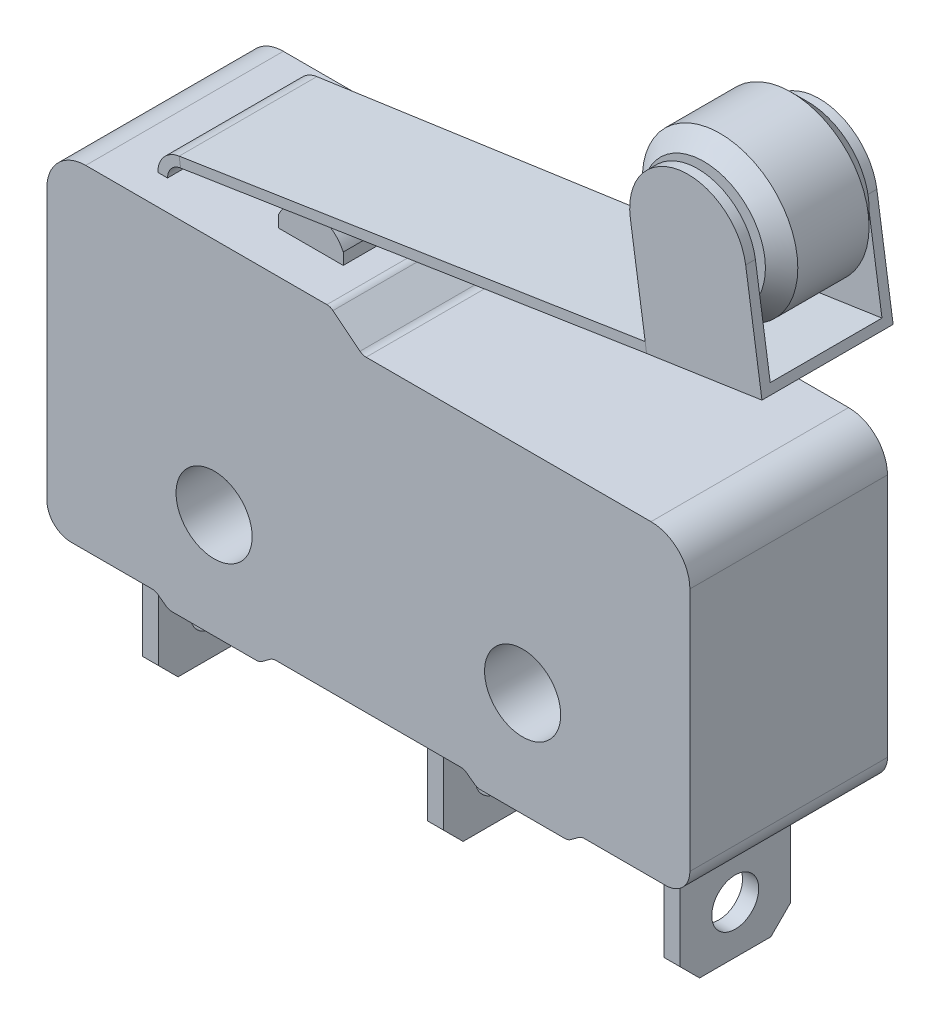
SolidWorks part; units mm, degrees
ref_plane "前视基准面" through (0, 0, 0) normal (0, 0, 1) x (1, 0, 0)
ref_plane "上视基准面" through (0, 0, 0) normal (0, 1, 0) x (1, 0, 0)
ref_plane "右视基准面" through (0, 0, 0) normal (1, 0, 0) x (0, 0, -1)
sketch "草图1" plane through (0, 0, 0) normal (0, 0, 1) x (1, 0, 0)
  line B0 (-3.0625, -6.8375) -> (-3.5625, -6.8375)
  line B1 (-3.5625, -6.2375) -> (-3.0625, -6.2375)
  line B2 (-3.0625, -6.8375) -> (-3.0625, -6.2375)
  line B3 (-3.5625, -6.8375) -> (-3.5625, -6.2375)
  line B4 (-3.0625, -6.2375) -> (-3.0625, -2.9375)
  line B5 (-3.5625, -6.2375) -> (-3.5625, -2.9375)
  line B6 (13.0375, -6.8375) -> (12.5375, -6.8375)
  line B7 (12.5375, -6.8375) -> (12.5375, -6.2375)
  line B8 (12.5375, -6.2375) -> (13.0375, -6.2375)
  line B9 (13.0375, -6.8375) -> (13.0375, -6.2375)
  line B10 (13.0375, -6.2375) -> (13.0375, -2.9375)
  line B11 (12.5375, -6.2375) -> (12.5375, -2.9375)
  line B12 (5.7375, -6.8375) -> (5.2375, -6.8375)
  line B13 (5.2375, -6.8375) -> (5.2375, -6.2375)
  line B14 (5.2375, -6.2375) -> (5.7375, -6.2375)
  line B15 (5.7375, -6.8375) -> (5.7375, -6.2375)
  line B16 (5.7375, -6.2375) -> (5.7375, -2.9375)
  line B17 (5.2375, -6.2375) -> (5.2375, -2.9375)
  line B18 (-2.6625, 6.5625) -> (-2.6625, 5.5625)
  line B19 (-2.3625, 6.5625) -> (-2.3625, 5.5625)
  line B20 (-1.9585, 7.8313) -> (-2.0029, 8.128)
  line B21 (-2.0029, 8.128) -> (1.8209, 8.6995)
  line B22 (1.8209, 8.6995) -> (1.8652, 8.4028)
  line B23 (1.8652, 8.4028) -> (-1.9585, 7.8313)
  line B24 (2.3154, 8.7734) -> (2.3597, 8.4767)
  line B25 (1.8209, 8.6995) -> (1.8704, 8.7069)
  line B26 (1.8704, 8.7069) -> (1.9301, 8.7158)
  line B27 (1.9301, 8.7158) -> (1.9968, 8.7258)
  line B28 (1.9968, 8.7258) -> (2.0673, 8.7363)
  line B29 (2.0673, 8.7363) -> (2.1379, 8.7469)
  line B30 (2.1379, 8.7469) -> (2.205, 8.7569)
  line B31 (2.205, 8.7569) -> (2.2652, 8.7659)
  line B32 (2.2652, 8.7659) -> (2.3154, 8.7734)
  line B33 (2.3597, 8.4767) -> (2.3095, 8.4692)
  line B34 (2.3095, 8.4692) -> (2.2493, 8.4602)
  line B35 (2.2493, 8.4602) -> (2.1822, 8.4502)
  line B36 (2.1822, 8.4502) -> (2.1116, 8.4396)
  line B37 (2.1116, 8.4396) -> (2.0412, 8.4291)
  line B38 (2.0412, 8.4291) -> (1.9744, 8.4191)
  line B39 (1.9744, 8.4191) -> (1.9147, 8.4102)
  line B40 (1.9147, 8.4102) -> (1.8652, 8.4028)
  line B41 (8.8923, 9.7563) -> (8.9367, 9.4596)
  line B42 (2.3154, 8.7734) -> (8.8923, 9.7563)
  line B43 (8.9367, 9.4596) -> (2.3597, 8.4767)
  line B44 (9.3869, 9.8302) -> (9.4312, 9.5335)
  line B45 (8.8923, 9.7563) -> (8.9367, 9.763)
  line B46 (8.9367, 9.763) -> (8.9954, 9.7717)
  line B47 (8.9954, 9.7717) -> (9.0643, 9.782)
  line B48 (9.0643, 9.782) -> (9.1386, 9.7931)
  line B49 (9.1386, 9.7931) -> (9.213, 9.8042)
  line B50 (9.213, 9.8042) -> (9.2823, 9.8146)
  line B51 (9.2823, 9.8146) -> (9.3416, 9.8235)
  line B52 (9.3416, 9.8235) -> (9.3869, 9.8302)
  line B53 (9.4312, 9.5335) -> (9.386, 9.5268)
  line B54 (9.386, 9.5268) -> (9.3266, 9.5179)
  line B55 (9.3266, 9.5179) -> (9.2573, 9.5075)
  line B56 (9.2573, 9.5075) -> (9.1829, 9.4964)
  line B57 (9.1829, 9.4964) -> (9.1087, 9.4853)
  line B58 (9.1087, 9.4853) -> (9.0398, 9.475)
  line B59 (9.0398, 9.475) -> (8.9811, 9.4663)
  line B60 (8.9811, 9.4663) -> (8.9367, 9.4596)
  line B61 (11.3926, 10.13) -> (11.4369, 9.8333)
  line B62 (9.3869, 9.8302) -> (11.3926, 10.13)
  line B63 (11.4369, 9.8333) -> (9.4312, 9.5335)
  line B64 (15.8284, 10.894) -> (12.2679, 10.3619)
  line B65 (15.8284, 10.894) -> (15.8399, 10.8169)
  line B66 (15.8399, 10.8169) -> (15.851, 10.7426)
  line B67 (15.851, 10.7426) -> (15.8612, 10.6742)
  line B68 (15.8612, 10.6742) -> (15.8702, 10.6143)
  line B69 (15.8702, 10.6143) -> (15.8775, 10.5651)
  line B70 (15.8775, 10.5651) -> (15.883, 10.5285)
  line B71 (15.883, 10.5285) -> (15.8864, 10.506)
  line B72 (15.8864, 10.506) -> (15.8875, 10.4984)
  line B73 (12.2827, 10.263) -> (12.2809, 10.2752)
  line B74 (12.2809, 10.2752) -> (12.2791, 10.2874)
  line B75 (12.2791, 10.2874) -> (12.2772, 10.2997)
  line B76 (12.2772, 10.2997) -> (12.2754, 10.3121)
  line B77 (12.2754, 10.3121) -> (12.2735, 10.3245)
  line B78 (12.2735, 10.3245) -> (12.2717, 10.3369)
  line B79 (12.2717, 10.3369) -> (12.2698, 10.3494)
  line B80 (12.2698, 10.3494) -> (12.2679, 10.3619)
  line B81 (12.2827, 10.263) -> (12.281, 10.2628)
  line B82 (15.8875, 10.4984) -> (11.8823, 9.8999)
  line B83 (11.3926, 10.13) -> (11.4165, 10.1336)
  line B84 (11.4165, 10.1336) -> (11.4647, 10.1408)
  line B85 (11.4647, 10.1408) -> (11.5346, 10.1512)
  line B86 (11.5346, 10.1512) -> (11.622, 10.1643)
  line B87 (11.622, 10.1643) -> (11.7219, 10.1792)
  line B88 (11.7219, 10.1792) -> (11.8285, 10.1951)
  line B89 (11.8285, 10.1951) -> (11.9357, 10.2112)
  line B90 (11.9357, 10.2112) -> (12.0372, 10.2263)
  line B91 (12.0372, 10.2263) -> (12.1272, 10.2398)
  line B92 (12.1272, 10.2398) -> (12.2005, 10.2507)
  line B93 (12.2005, 10.2507) -> (12.2528, 10.2585)
  line B94 (12.2528, 10.2585) -> (12.281, 10.2628)
  line B95 (11.8823, 9.8999) -> (11.8006, 9.8876)
  line B96 (11.8006, 9.8876) -> (11.7217, 9.8758)
  line B97 (11.7217, 9.8758) -> (11.6481, 9.8648)
  line B98 (11.6481, 9.8648) -> (11.5824, 9.855)
  line B99 (11.5824, 9.855) -> (11.5268, 9.8467)
  line B100 (11.5268, 9.8467) -> (11.4831, 9.8402)
  line B101 (11.4831, 9.8402) -> (11.4528, 9.8357)
  line B102 (11.4528, 9.8357) -> (11.4369, 9.8333)
  line B103 (12.2679, 10.3619) -> (11.8245, 13.329)
  line B104 (15.3849, 13.8611) -> (15.8284, 10.894)
  line B105 (0.6875, 7.3625) -> (0.6875, 7.7208)
  line B106 (2.6875, 7.7208) -> (2.6875, 7.3625)
  line B107 (8.0461, -3.1801) -> (7.7914, -2.9949)
  line B108 (7.7125, -2.9538) -> (7.7125, 0)
  line B109 (11.3375, 0) -> (11.3375, -2.9538)
  line B110 (11.0039, -3.1801) -> (11.2586, -2.9949)
  line B111 (8.2226, -3.2375) -> (10.8274, -3.2375)
  line B112 (-1.8125, -2.9538) -> (-1.8125, 0)
  line B113 (1.8125, 0) -> (1.8125, -2.9538)
  line B114 (1.4789, -3.1801) -> (1.7336, -2.9949)
  line B115 (-1.3024, -3.2375) -> (1.3024, -3.2375)
  line B116 (-1.4789, -3.1801) -> (-1.7336, -2.9949)
  line B117 (-2.7625, 6.5625) -> (-2.2125, 6.5625)
  line B118 (-2.7625, 5.5625) -> (-2.7625, 6.5625)
  line B119 (-2.2125, 5.5625) -> (-2.7625, 5.5625)
  line B120 (-2.2125, 6.5625) -> (-2.2125, 5.5625)
  line B121 (12.2347, -2.683) -> (12.0611, -2.683)
  line B122 (12.0611, -2.683) -> (12.0611, -1.283)
  line B123 (12.0611, -1.283) -> (12.3254, -1.283)
  line B124 (12.3254, -1.283) -> (12.8893, -2.3914)
  line B125 (12.8893, -2.3914) -> (12.8893, -1.283)
  line B126 (12.8893, -1.283) -> (13.0629, -1.283)
  line B127 (13.0629, -1.283) -> (13.0629, -2.683)
  line B128 (12.8541, -2.683) -> (13.0629, -2.683)
  line B129 (12.8541, -2.683) -> (12.2347, -1.4759)
  line B130 (12.2347, -1.4759) -> (12.2347, -2.683)
  line B131 (4.9647, -2.6875) -> (4.7911, -2.6875)
  line B132 (4.7911, -2.6875) -> (4.7911, -1.2875)
  line B133 (5.6193, -2.396) -> (5.6193, -1.2875)
  line B134 (5.6193, -1.2875) -> (5.7929, -1.2875)
  line B135 (5.7929, -1.2875) -> (5.7929, -2.6875)
  line B136 (5.5841, -2.6875) -> (5.7929, -2.6875)
  line B137 (5.5841, -2.6875) -> (4.9647, -1.4804)
  line B138 (4.9647, -1.4804) -> (4.9647, -2.6875)
  line B139 (5.0555, -1.2875) -> (5.6193, -2.396)
  line B140 (4.7911, -1.2875) -> (5.0555, -1.2875)
  line B141 (-2.8296, -1.376) -> (-2.8296, -1.6007)
  line B142 (-2.8296, -1.6007) -> (-2.8443, -1.6007)
  line B143 (-2.8432, -2.3653) -> (-2.8296, -2.3653)
  line B144 (-2.8296, -2.3653) -> (-2.8296, -2.5877)
  line B145 (14.329, -1.6007) -> (14.3142, -1.6007)
  line B146 (14.3154, -2.3653) -> (14.329, -2.3653)
  line B147 (14.329, -2.3653) -> (14.329, -2.5877)
  line B148 (14.329, -1.376) -> (14.329, -1.6007)
  line B149 (13.4875, 6.5625) -> (4.6927, 6.5625)
  line B150 (-5.1625, 6.1625) -> (-5.1625, -2.1875)
  line B151 (1.9101, -2.9375) -> (7.6149, -2.9375)
  line B152 (3.6697, 7.2968) -> (4.5053, 6.6282)
  line B153 (3.4823, 7.3625) -> (-3.9625, 7.3625)
  line B154 (14.6875, -2.1875) -> (14.6875, 5.3625)
  line B155 (-4.4125, -2.9375) -> (-1.9101, -2.9375)
  line B156 (11.4351, -2.9375) -> (13.9375, -2.9375)
  arc B157 (15.6196, 12.2911) -> (11.9739, 15.3558) centre (13.6047, 13.595) ccw
  arc B158 (11.9739, 15.3558) -> (12.0591, 11.759) centre (13.6047, 13.595) ccw
  arc B159 (15.4749, 13.2595) -> (12.3137, 14.989) centre (13.6047, 13.595) ccw
  arc B160 (12.3137, 14.989) -> (11.9144, 12.7274) centre (13.6047, 13.595) ccw
  circle B161 centre (13.6047, 13.595) radius 1.5
  arc B162 (-2.0029, 8.128) -> (-2.6625, 7.3625) centre (-1.8885, 7.3625) ccw
  arc B163 (-1.9585, 7.8313) -> (-2.3625, 7.3625) centre (-1.8885, 7.3625) ccw
  arc B164 (15.3849, 13.8611) -> (11.8245, 13.329) centre (13.6047, 13.595) ccw
  arc B165 (2.6875, 7.7208) -> (0.6875, 7.7208) centre (1.6875, 7.2625) ccw
  arc B166 (7.7914, -2.9949) -> (7.7125, -2.9538) centre (7.6149, -3.2375) ccw
  arc B167 (11.3375, 0) -> (7.7125, 0) centre (9.525, -0.0003) ccw
  arc B168 (11.3375, -2.9538) -> (11.2586, -2.9949) centre (11.4351, -3.2375) ccw
  arc B169 (10.8274, -3.2375) -> (11.0039, -3.1801) centre (10.8274, -2.9375) ccw
  arc B170 (8.0461, -3.1801) -> (8.2226, -3.2375) centre (8.2226, -2.9375) ccw
  circle B171 centre (9.525, 0) radius 1.175
  arc B172 (1.8125, 0) -> (-1.8125, 0) centre (0, 0) ccw
  arc B173 (1.8125, -2.9538) -> (1.7336, -2.9949) centre (1.9101, -3.2375) ccw
  arc B174 (1.3024, -3.2375) -> (1.4789, -3.1801) centre (1.3024, -2.9375) ccw
  arc B175 (-1.4789, -3.1801) -> (-1.3024, -3.2375) centre (-1.3024, -2.9375) ccw
  arc B176 (-1.7336, -2.9949) -> (-1.8125, -2.9538) centre (-1.9101, -3.2375) ccw
  circle B177 centre (0, 0) radius 1.175
  circle B178 centre (-2.3625, 6.2625) radius 1.1
  arc B179 (3.6697, 7.2968) -> (3.4823, 7.3625) centre (3.4823, 7.0625) ccw
  arc B180 (4.5053, 6.6282) -> (4.6927, 6.5625) centre (4.6927, 6.8625) ccw
  arc B181 (14.6875, 5.3625) -> (13.4875, 6.5625) centre (13.4875, 5.3625) ccw
  arc B182 (-3.9625, 7.3625) -> (-5.1625, 6.1625) centre (-3.9625, 6.1625) ccw
  arc B183 (13.9375, -2.9375) -> (14.6875, -2.1875) centre (13.9375, -2.1875) ccw
  arc B184 (-5.1625, -2.1875) -> (-4.4125, -2.9375) centre (-4.4125, -2.1875) ccw
  arc B185 (1.9101, -2.9375) -> (1.8125, -2.9538) centre (1.9101, -3.2375) ccw
  arc B186 (11.4351, -2.9375) -> (11.3375, -2.9538) centre (11.4351, -3.2375) ccw
  arc B187 (7.7125, -2.9538) -> (7.6149, -2.9375) centre (7.6149, -3.2375) ccw
  arc B188 (-1.8125, -2.9538) -> (-1.9101, -2.9375) centre (-1.9101, -3.2375) ccw
  spline B189 degree 3 poles (12.281, 10.2628) (12.2847, 10.2234) (12.292, 10.1445) (12.2789, 10.0506) (12.2332, 9.987) (12.1569, 9.9489) (12.0515, 9.925) (11.9539, 9.9106) (11.8951, 9.9018) (11.8823, 9.8999) knots 0 0 0 0 0.160969 0.322392 0.472546 0.614631 0.770013 0.950189 1 1 1 1
  spline B190 degree 3 poles (-3.7168, -1.4509) (-3.6608, -1.3881) (-3.5946, -1.3403) (-3.4419, -1.2745) (-3.3564, -1.258) (-3.2618, -1.258) knots -2 -2 -2 -2 -1 -1 0 0 0 0
  spline B191 degree 3 poles (-3.2618, -1.258) (-3.215, -1.258) (-3.1709, -1.2614) (-3.0885, -1.2751) (-3.0504, -1.2837) (-3.0157, -1.2943) knots -2 -2 -2 -2 -1 -1 0 0 0 0
  spline B192 degree 3 poles (-3.0157, -1.2943) (-2.9854, -1.3042) (-2.9546, -1.3161) (-2.8918, -1.3441) (-2.8606, -1.3594) (-2.8296, -1.376) knots -2 -2 -2 -2 -1 -1 0 0 0 0
  spline B193 degree 3 poles (-2.8443, -1.6007) (-2.861, -1.5855) (-2.8822, -1.5674) (-2.9336, -1.525) (-2.965, -1.5042) (-3.002, -1.4838) knots -2 -2 -2 -2 -1 -1 0 0 0 0
  spline B194 degree 3 poles (-3.002, -1.4838) (-3.0376, -1.4641) (-3.0763, -1.4481) (-3.1603, -1.4231) (-3.2085, -1.4169) (-3.263, -1.4169) knots -2 -2 -2 -2 -1 -1 0 0 0 0
  spline B195 degree 3 poles (-3.263, -1.4169) (-3.3227, -1.4169) (-3.3793, -1.4292) (-3.4859, -1.4783) (-3.5326, -1.5141) (-3.5727, -1.561) knots -2 -2 -2 -2 -1 -1 0 0 0 0
  spline B196 degree 3 poles (-3.5727, -1.561) (-3.612, -1.6086) (-3.6427, -1.6685) (-3.6865, -1.813) (-3.6975, -1.8941) (-3.6975, -1.9841) knots -2 -2 -2 -2 -1 -1 0 0 0 0
  spline B197 degree 3 poles (-3.6975, -1.9841) (-3.6975, -2.0802) (-3.686, -2.1628) (-3.6398, -2.3012) (-3.6083, -2.3597) (-3.5682, -2.4073) knots -2 -2 -2 -2 -1 -1 0 0 0 0
  spline B198 degree 3 poles (-3.5682, -2.4073) (-3.5288, -2.4534) (-3.4829, -2.4882) (-3.3778, -2.5351) (-3.322, -2.5469) (-3.263, -2.5469) knots -2 -2 -2 -2 -1 -1 0 0 0 0
  spline B199 degree 3 poles (-3.263, -2.5469) (-3.2093, -2.5469) (-3.1595, -2.5402) (-3.068, -2.5138) (-3.0274, -2.4973) (-2.9918, -2.4776) knots -2 -2 -2 -2 -1 -1 0 0 0 0
  spline B200 degree 3 poles (-2.9918, -2.4776) (-2.9578, -2.458) (-2.9281, -2.4379) (-2.8774, -2.3971) (-2.8576, -2.3797) (-2.8432, -2.3653) knots -2 -2 -2 -2 -1 -1 0 0 0 0
  spline B201 degree 3 poles (-2.8296, -2.5877) (-2.8606, -2.6021) (-2.8897, -2.6159) (-2.9442, -2.6423) (-2.9771, -2.655) (-3.0157, -2.6671) knots -2 -2 -2 -2 -1 -1 0 0 0 0
  spline B202 degree 3 poles (-3.0157, -2.6671) (-3.0565, -2.6807) (-3.0943, -2.6909) (-3.1639, -2.7045) (-3.2093, -2.708) (-3.2652, -2.708) knots -2 -2 -2 -2 -1 -1 0 0 0 0
  spline B203 degree 3 poles (-3.2652, -2.708) (-3.356, -2.708) (-3.4398, -2.6926) (-3.5933, -2.6314) (-3.6597, -2.5854) (-3.7157, -2.5242) knots -2 -2 -2 -2 -1 -1 0 0 0 0
  spline B204 degree 3 poles (-3.7157, -2.5242) (-3.7716, -2.4637) (-3.8149, -2.388) (-3.8762, -2.2065) (-3.8915, -2.1021) (-3.8915, -1.9841) knots -2 -2 -2 -2 -1 -1 0 0 0 0
  spline B205 degree 3 poles (-3.8915, -1.9841) (-3.8915, -1.8669) (-3.8766, -1.7648) (-3.8168, -1.5908) (-3.7735, -1.5152) (-3.7168, -1.4509) knots -2 -2 -2 -2 -1 -1 0 0 0 0
  spline B206 degree 3 poles (13.4418, -1.4509) (13.4978, -1.3881) (13.5639, -1.3403) (13.7167, -1.2745) (13.8022, -1.258) (13.8967, -1.258) knots -2 -2 -2 -2 -1 -1 0 0 0 0
  spline B207 degree 3 poles (13.8967, -1.258) (13.9436, -1.258) (13.9877, -1.2614) (14.0701, -1.2751) (14.1081, -1.2837) (14.1429, -1.2943) knots -2 -2 -2 -2 -1 -1 0 0 0 0
  spline B208 degree 3 poles (14.1429, -1.2943) (14.1732, -1.3042) (14.204, -1.3161) (14.2668, -1.3441) (14.298, -1.3594) (14.329, -1.376) knots -2 -2 -2 -2 -1 -1 0 0 0 0
  spline B209 degree 3 poles (14.3142, -1.6007) (14.2976, -1.5855) (14.2764, -1.5674) (14.225, -1.525) (14.1936, -1.5042) (14.1565, -1.4838) knots -2 -2 -2 -2 -1 -1 0 0 0 0
  spline B210 degree 3 poles (14.1565, -1.4838) (14.121, -1.4641) (14.0822, -1.4481) (13.9983, -1.4231) (13.9501, -1.4169) (13.8956, -1.4169) knots -2 -2 -2 -2 -1 -1 0 0 0 0
  spline B211 degree 3 poles (13.8956, -1.4169) (13.8358, -1.4169) (13.7793, -1.4292) (13.6727, -1.4783) (13.626, -1.5141) (13.5859, -1.561) knots -2 -2 -2 -2 -1 -1 0 0 0 0
  spline B212 degree 3 poles (13.5859, -1.561) (13.5465, -1.6086) (13.5159, -1.6685) (13.472, -1.813) (13.4611, -1.8941) (13.4611, -1.9841) knots -2 -2 -2 -2 -1 -1 0 0 0 0
  spline B213 degree 3 poles (13.4611, -1.9841) (13.4611, -2.0802) (13.4726, -2.1628) (13.5187, -2.3012) (13.5503, -2.3597) (13.5904, -2.4073) knots -2 -2 -2 -2 -1 -1 0 0 0 0
  spline B214 degree 3 poles (13.5904, -2.4073) (13.6297, -2.4534) (13.6757, -2.4882) (13.7808, -2.5351) (13.8366, -2.5469) (13.8956, -2.5469) knots -2 -2 -2 -2 -1 -1 0 0 0 0
  spline B215 degree 3 poles (13.8956, -2.5469) (13.9493, -2.5469) (13.999, -2.5402) (14.0905, -2.5138) (14.1312, -2.4973) (14.1667, -2.4776) knots -2 -2 -2 -2 -1 -1 0 0 0 0
  spline B216 degree 3 poles (14.1667, -2.4776) (14.2008, -2.458) (14.2305, -2.4379) (14.2811, -2.3971) (14.301, -2.3797) (14.3154, -2.3653) knots -2 -2 -2 -2 -1 -1 0 0 0 0
  spline B217 degree 3 poles (14.329, -2.5877) (14.298, -2.6021) (14.2689, -2.6159) (14.2144, -2.6423) (14.1815, -2.655) (14.1429, -2.6671) knots -2 -2 -2 -2 -1 -1 0 0 0 0
  spline B218 degree 3 poles (14.1429, -2.6671) (14.1021, -2.6807) (14.0643, -2.6909) (13.9947, -2.7045) (13.9493, -2.708) (13.8933, -2.708) knots -2 -2 -2 -2 -1 -1 0 0 0 0
  spline B219 degree 3 poles (13.8933, -2.708) (13.8026, -2.708) (13.7188, -2.6926) (13.5653, -2.6314) (13.4989, -2.5854) (13.4429, -2.5242) knots -2 -2 -2 -2 -1 -1 0 0 0 0
  spline B220 degree 3 poles (13.4429, -2.5242) (13.3869, -2.4637) (13.3436, -2.388) (13.2824, -2.2065) (13.2671, -2.1021) (13.2671, -1.9841) knots -2 -2 -2 -2 -1 -1 0 0 0 0
  spline B221 degree 3 poles (13.2671, -1.9841) (13.2671, -1.8669) (13.282, -1.7648) (13.3418, -1.5908) (13.3851, -1.5152) (13.4418, -1.4509) knots -2 -2 -2 -2 -1 -1 0 0 0 0
  spline B222 degree 3 poles (6.165, -1.4475) (6.2195, -1.3855) (6.2847, -1.3384) (6.4367, -1.2741) (6.5216, -1.258) (6.6154, -1.258) knots -2 -2 -2 -2 -1 -1 0 0 0 0
  spline B223 degree 3 poles (6.6154, -1.258) (6.7107, -1.258) (6.7966, -1.2747) (6.9494, -1.3412) (7.014, -1.3877) (7.067, -1.4475) knots -2 -2 -2 -2 -1 -1 0 0 0 0
  spline B224 degree 3 poles (7.067, -1.4475) (7.1199, -1.5095) (7.1611, -1.5859) (7.2201, -1.7674) (7.2349, -1.8711) (7.2349, -1.9875) knots -2 -2 -2 -2 -1 -1 0 0 0 0
  spline B225 degree 3 poles (7.2349, -1.9875) (7.2349, -2.101) (7.2205, -2.2037) (7.163, -2.3875) (7.1214, -2.4644) (7.067, -2.5264) knots -2 -2 -2 -2 -1 -1 0 0 0 0
  spline B226 degree 3 poles (6.9263, -1.5644) (6.9626, -1.6112) (6.9908, -1.6704) (7.0309, -1.8134) (7.0409, -1.8953) (7.0409, -1.9875) knots 0 0 0 0 1 1 2 2 2 2
  spline B227 degree 3 poles (6.6166, -1.4191) (6.6816, -1.4191) (6.7402, -1.4312) (6.8446, -1.4796) (6.8892, -1.5159) (6.9263, -1.5644) knots 0 0 0 0 1 1 2 2 2 2
  spline B228 degree 3 poles (6.6154, -2.717) (6.5209, -2.717) (6.4358, -2.701) (6.2845, -2.6367) (6.2191, -2.5892) (6.1639, -2.5264) knots -2 -2 -2 -2 -1 -1 0 0 0 0
  spline B229 degree 3 poles (7.067, -2.5264) (7.0095, -2.5915) (6.9427, -2.6395) (6.7907, -2.7015) (6.7069, -2.717) (6.6154, -2.717) knots -2 -2 -2 -2 -1 -1 0 0 0 0
  spline B230 degree 3 poles (6.3057, -1.5644) (6.3443, -1.5144) (6.3889, -1.4778) (6.4903, -1.4309) (6.5492, -1.4191) (6.6166, -1.4191) knots 0 0 0 0 1 1 2 2 2 2
  spline B231 degree 3 poles (6.1639, -2.5264) (6.1102, -2.4644) (6.069, -2.3878) (6.0115, -2.2055) (5.9971, -2.1025) (5.9971, -1.9875) knots -2 -2 -2 -2 -1 -1 0 0 0 0
  spline B232 degree 3 poles (6.6166, -2.5559) (6.4872, -2.5559) (6.384, -2.5071) (6.2297, -2.312) (6.1911, -2.1713) (6.1911, -1.9875) knots 0 0 0 0 1 1 2 2 2 2
  spline B233 degree 3 poles (6.1911, -1.9875) (6.1911, -1.8968) (6.2009, -1.8155) (6.2403, -1.6718) (6.2686, -1.612) (6.3057, -1.5644) knots 0 0 0 0 1 1 2 2 2 2
  spline B234 degree 3 poles (5.9971, -1.9875) (5.9971, -1.8703) (6.0117, -1.7671) (6.0699, -1.5886) (6.1113, -1.5118) (6.165, -1.4475) knots -2 -2 -2 -2 -1 -1 0 0 0 0
  spline B235 degree 3 poles (7.0409, -1.9875) (7.0409, -2.1713) (7.0025, -2.312) (6.8489, -2.5071) (6.7459, -2.5559) (6.6166, -2.5559) knots 0 0 0 0 1 1 2 2 2 2
sketch_block_instance "块1-1"
sketch_block "块1"
sketch "草图2" plane through (0, 0, 0) normal (0, 0, 1) x (1, 0, 0)
  line L0 (13.4875, 6.5625) -> (4.6927, 6.5625) construction
  line L1 (14.6875, -2.1875) -> (14.6875, 5.3625) construction
  line L2 (11.4351, -2.9375) -> (13.9375, -2.9375) construction
  line L3 (11.0039, -3.1801) -> (11.2586, -2.9949) construction
  line L4 (8.2226, -3.2375) -> (10.8274, -3.2375) construction
  line L5 (8.0461, -3.1801) -> (7.7914, -2.9949) construction
  line L6 (1.9101, -2.9375) -> (7.6149, -2.9375) construction
  line L7 (1.4789, -3.1801) -> (1.7336, -2.9949) construction
  line L8 (-1.3024, -3.2375) -> (1.3024, -3.2375) construction
  line L9 (-1.4789, -3.1801) -> (-1.7336, -2.9949) construction
  line L10 (-4.4125, -2.9375) -> (-1.9101, -2.9375) construction
  line L11 (-5.1625, 6.1625) -> (-5.1625, -2.1875) construction
  line L12 (3.4823, 7.3625) -> (-3.9625, 7.3625) construction
  line L13 (3.6697, 7.2968) -> (4.5053, 6.6282) construction
  line L14 (13.4875, 6.5625) -> (4.6927, 6.5625)
  line L15 (14.6875, -2.1875) -> (14.6875, 5.3625)
  line L16 (11.4351, -2.9375) -> (13.9375, -2.9375)
  line L17 (11.0039, -3.1801) -> (11.2586, -2.9949)
  line L18 (8.2226, -3.2375) -> (10.8274, -3.2375)
  line L19 (8.0461, -3.1801) -> (7.7914, -2.9949)
  line L20 (1.9101, -2.9375) -> (7.6149, -2.9375)
  line L21 (1.4789, -3.1801) -> (1.7336, -2.9949)
  line L22 (-1.3024, -3.2375) -> (1.3024, -3.2375)
  line L23 (-1.4789, -3.1801) -> (-1.7336, -2.9949)
  line L24 (-4.4125, -2.9375) -> (-1.9101, -2.9375)
  line L25 (-5.1625, 6.1625) -> (-5.1625, -2.1875)
  line L26 (3.4823, 7.3625) -> (-3.9625, 7.3625)
  line L27 (3.6697, 7.2968) -> (4.5053, 6.6282)
  circle A0 centre (0, 0) radius 1.175 construction
  circle A1 centre (9.525, 0) radius 1.175 construction
  arc A2 (14.6875, 5.3625) -> (13.4875, 6.5625) centre (13.4875, 5.3625) ccw construction
  arc A3 (13.9375, -2.9375) -> (14.6875, -2.1875) centre (13.9375, -2.1875) ccw construction
  arc A4 (10.8274, -3.2375) -> (11.0039, -3.1801) centre (10.8274, -2.9375) ccw construction
  arc A5 (11.3375, -2.9538) -> (11.2586, -2.9949) centre (11.4351, -3.2375) ccw construction
  arc A6 (11.4351, -2.9375) -> (11.3375, -2.9538) centre (11.4351, -3.2375) ccw construction
  arc A7 (8.0461, -3.1801) -> (8.2226, -3.2375) centre (8.2226, -2.9375) ccw construction
  arc A8 (7.7914, -2.9949) -> (7.7125, -2.9538) centre (7.6149, -3.2375) ccw construction
  arc A9 (7.7125, -2.9538) -> (7.6149, -2.9375) centre (7.6149, -3.2375) ccw construction
  arc A10 (1.8125, -2.9538) -> (1.7336, -2.9949) centre (1.9101, -3.2375) ccw construction
  arc A11 (1.9101, -2.9375) -> (1.8125, -2.9538) centre (1.9101, -3.2375) ccw construction
  arc A12 (1.3024, -3.2375) -> (1.4789, -3.1801) centre (1.3024, -2.9375) ccw construction
  arc A13 (-1.4789, -3.1801) -> (-1.3024, -3.2375) centre (-1.3024, -2.9375) ccw construction
  arc A14 (-1.7336, -2.9949) -> (-1.8125, -2.9538) centre (-1.9101, -3.2375) ccw construction
  arc A15 (-1.8125, -2.9538) -> (-1.9101, -2.9375) centre (-1.9101, -3.2375) ccw construction
  arc A16 (-5.1625, -2.1875) -> (-4.4125, -2.9375) centre (-4.4125, -2.1875) ccw construction
  arc A17 (-3.9625, 7.3625) -> (-5.1625, 6.1625) centre (-3.9625, 6.1625) ccw construction
  arc A18 (3.6697, 7.2968) -> (3.4823, 7.3625) centre (3.4823, 7.0625) ccw construction
  arc A19 (4.5053, 6.6282) -> (4.6927, 6.5625) centre (4.6927, 6.8625) ccw construction
  circle A20 centre (0, 0) radius 1.175
  circle A21 centre (9.525, 0) radius 1.175
  arc A22 (14.6875, 5.3625) -> (13.4875, 6.5625) centre (13.4875, 5.3625) ccw
  arc A23 (13.9375, -2.9375) -> (14.6875, -2.1875) centre (13.9375, -2.1875) ccw
  arc A24 (10.8274, -3.2375) -> (11.0039, -3.1801) centre (10.8274, -2.9375) ccw
  arc A25 (11.3375, -2.9538) -> (11.2586, -2.9949) centre (11.4351, -3.2375) ccw
  arc A26 (11.4351, -2.9375) -> (11.3375, -2.9538) centre (11.4351, -3.2375) ccw
  arc A27 (8.0461, -3.1801) -> (8.2226, -3.2375) centre (8.2226, -2.9375) ccw
  arc A28 (7.7914, -2.9949) -> (7.7125, -2.9538) centre (7.6149, -3.2375) ccw
  arc A29 (7.7125, -2.9538) -> (7.6149, -2.9375) centre (7.6149, -3.2375) ccw
  arc A30 (1.8125, -2.9538) -> (1.7336, -2.9949) centre (1.9101, -3.2375) ccw
  arc A31 (1.9101, -2.9375) -> (1.8125, -2.9538) centre (1.9101, -3.2375) ccw
  arc A32 (1.3024, -3.2375) -> (1.4789, -3.1801) centre (1.3024, -2.9375) ccw
  arc A33 (-1.4789, -3.1801) -> (-1.3024, -3.2375) centre (-1.3024, -2.9375) ccw
  arc A34 (-1.7336, -2.9949) -> (-1.8125, -2.9538) centre (-1.9101, -3.2375) ccw
  arc A35 (-1.8125, -2.9538) -> (-1.9101, -2.9375) centre (-1.9101, -3.2375) ccw
  arc A36 (-5.1625, -2.1875) -> (-4.4125, -2.9375) centre (-4.4125, -2.1875) ccw
  arc A37 (-3.9625, 7.3625) -> (-5.1625, 6.1625) centre (-3.9625, 6.1625) ccw
  arc A38 (3.6697, 7.2968) -> (3.4823, 7.3625) centre (3.4823, 7.0625) ccw
  arc A39 (4.5053, 6.6282) -> (4.6927, 6.5625) centre (4.6927, 6.8625) ccw
extrude "凸台-拉伸1" add sketch "草图2" along normal mid plane 6.1
sketch "草图3" plane through (0, 0, 0) normal (0, 0, 1) x (1, 0, 0)
  line L1 (-3.5625, -2.9375) -> (-3.0625, -2.9375)
  line L2 (-3.5625, -2.9375) -> (-3.5625, -6.8375)
  line L3 (-3.5625, -6.8375) -> (-3.0625, -6.8375)
  line L4 (-3.0625, -2.9375) -> (-3.0625, -6.8375)
  line L5 (5.2375, -2.9375) -> (5.7375, -2.9375)
  line L6 (5.2375, -2.9375) -> (5.2375, -6.8375)
  line L7 (5.2375, -6.8375) -> (5.7375, -6.8375)
  line L8 (5.7375, -2.9375) -> (5.7375, -6.8375)
  line L9 (12.5375, -2.9375) -> (13.0375, -2.9375)
  line L10 (12.5375, -2.9375) -> (12.5375, -6.8375)
  line L11 (12.5375, -6.8375) -> (13.0375, -6.8375)
  line L12 (13.0375, -2.9375) -> (13.0375, -6.8375)
extrude "凸台-拉伸2" add sketch "草图3" along normal mid plane 3.4
chamfer "倒角1" distance 0.6 angle 45 6 edges at (-3.3125, -6.8375, -1.7) (5.4875, -6.8375, -1.7) (12.7875, -6.8375, -1.7) (12.7875, -6.8375, 1.7) (5.4875, -6.8375, 1.7) (-3.3125, -6.8375, 1.7)
sketch "草图4" plane through (13.0375, 0, 0) normal (1, 0, 0) x (0, 0, -1)
  line L0 (-1.1, -6.8375) -> (1.1, -6.8375) construction
  line L1 (-1.7, -6.2375) -> (-1.7, -2.9375) construction
  circle A0 centre (0, -5.3575) radius 0.725
  dimension "D2" = 1.45
  dimension "D1" = 1.48
  dimension "D3" = 1.7
extrude "切除-拉伸1" cut sketch "草图4" against normal through all
sketch "草图5" plane through (0, 0, 0) normal (0, 0, 1) x (1, 0, 0)
  line L1 (-2.0029, 8.128) -> (1.8209, 8.6995) construction
  line L2 (1.8652, 8.4028) -> (-1.9585, 7.8313) construction
  line L3 (3.4823, 7.3625) -> (-3.9625, 7.3625) construction
  line L4 (15.3849, 13.8611) -> (15.8284, 10.894) construction
  line L6 (-2.0029, 8.128) -> (15.8432, 10.7951)
  line L7 (15.8875, 10.4984) -> (-1.9585, 7.8313)
  line L8 (-2.3625, 7.3625) -> (-2.6625, 7.3625)
  line L9 (15.8432, 10.7951) -> (15.8875, 10.4984)
  arc A0 (-2.0029, 8.128) -> (-2.6625, 7.3625) centre (-1.8885, 7.3625) ccw construction
  arc A1 (-1.9585, 7.8313) -> (-2.3625, 7.3625) centre (-1.8885, 7.3625) ccw construction
  arc A2 (-2.0029, 8.128) -> (-2.6625, 7.3625) centre (-1.8885, 7.3625) ccw
  arc A3 (-1.9585, 7.8313) -> (-2.3625, 7.3625) centre (-1.8885, 7.3625) ccw
extrude "凸台-拉伸3" add sketch "草图5" along normal mid plane 4.25
sketch "草图6" plane through (-1.232, 8.2432, 0) normal (-0.1478, 0.989, 0) x (0.989, 0.1478, 0)
  line L0 (17.2648, 2.025) -> (13.6648, 2.025)
  line L1 (17.2648, -2.125) -> (17.2648, 2.125) construction
  line L2 (0, 0) -> (20.5747, 0) construction
  line L3 (13.6648, -2.025) -> (17.2648, -2.025)
  line L4 (13.6648, 2.025) -> (-0.7795, 2.125)
  line L5 (-0.7795, 2.125) -> (17.2648, 2.125)
  line L6 (17.2648, 2.125) -> (17.2648, 2.025)
  line L7 (13.6648, -2.025) -> (-0.7795, -2.125)
  line L8 (-1.545, -2.125) -> (-0.7795, -2.125) construction
  line L9 (-0.7795, -2.125) -> (-0.7795, 2.125) construction
  line L10 (-0.7795, -2.125) -> (17.2648, -2.125)
  line L11 (17.2648, -2.125) -> (17.2648, -2.025)
  dimension "D1" = 4.05
  dimension "D2" = 3.6
extrude "切除-拉伸2" cut sketch "草图6" against normal up to vertex
sketch "草图7" plane through (0, 0, 2.025) normal (0, 0, 1) x (1, 0, 0)
  line L0 (15.3849, 13.8611) -> (15.8284, 10.894) construction
  line L1 (12.2679, 10.3619) -> (11.8245, 13.329) construction
  line L2 (15.8875, 10.4984) -> (11.8823, 9.8999) construction
  line L3 (15.3849, 13.8611) -> (15.8875, 10.4984)
  line L4 (12.327, 9.9663) -> (11.8245, 13.329)
  line L5 (15.8875, 10.4984) -> (12.327, 9.9663)
  arc A0 (15.3849, 13.8611) -> (11.8245, 13.329) centre (13.6047, 13.595) ccw construction
  arc A1 (15.3849, 13.8611) -> (11.8245, 13.329) centre (13.6047, 13.595) ccw
extrude "凸台-拉伸4" add sketch "草图7" against normal blind 0.3
mirror "镜向2" about plane through (0, 0, 0) normal (0, 0, 1) of "凸台-拉伸4"
ref_axis "基准轴1" through (13.6047, 13.595, -1.725) along (0, 0, -1)
ref_plane "基准面2" through (-1.6902, 11.3092, 0) normal (-0.1478, 0.989, 0) x (0.989, 0.1478, 0)
sketch "草图8" plane through (-1.6902, 11.3092, 0) normal (-0.1478, 0.989, 0) x (0.989, 0.1478, 0)
  line L0 (15.4648, 1.665) -> (15.4648, -1.535)
  line L1 (15.4648, 1.725) -> (15.4648, 2.025) construction
  line L2 (15.4648, -1.535) -> (13.5648, -1.535)
  line L3 (13.5648, -1.535) -> (13.0648, -1.035)
  line L4 (13.0648, -1.035) -> (13.0648, 1.165)
  line L5 (13.0648, 1.165) -> (13.5648, 1.665)
  line L6 (13.5648, 1.665) -> (15.4648, 1.665)
  line L7 (13.6648, 1.725) -> (17.2648, 1.725) construction
  dimension "D1" = 45
  dimension "D2" = 45
  dimension "D3" = 2.4
  dimension "D4" = 0.06
  dimension "D5" = 3.2
  dimension "D6" = 0.5
  dimension "D7" = 0.5
revolve "旋转1" add sketch "草图8" angle 360 about axis through (13.6047, 13.595, -1.725) along (0, 0, -1)
sketch "草图9" plane through (0, 0, 0) normal (0, 0, 1) x (1, 0, 0)
  line L0 (2.6875, 7.7208) -> (2.6875, 7.3625) construction
  line L1 (0.6875, 7.3625) -> (0.6875, 7.7208) construction
  line L2 (2.6875, 7.7208) -> (2.6875, 7.3625)
  line L3 (0.6875, 7.3625) -> (0.6875, 7.7208)
  line L4 (0.6875, 7.3625) -> (2.6875, 7.3625)
  arc A0 (2.6875, 7.7208) -> (0.6875, 7.7208) centre (1.6875, 7.2625) ccw construction
  arc A1 (2.6875, 7.7208) -> (0.6875, 7.7208) centre (1.6875, 7.2625) ccw
extrude "凸台-拉伸5" add sketch "草图9" along normal mid plane 3.5
